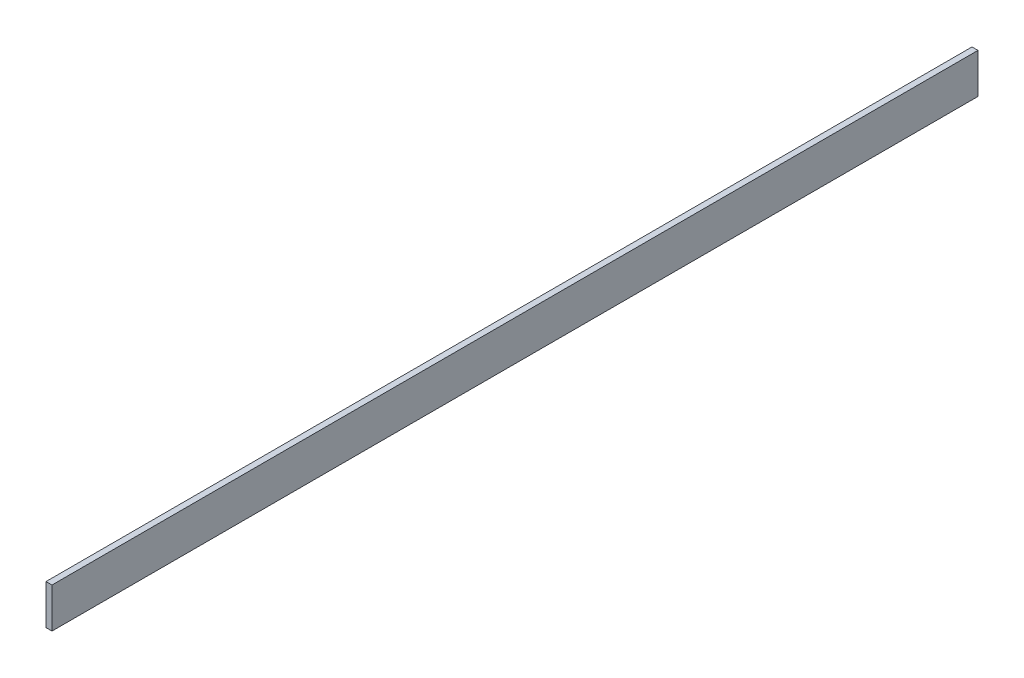
SolidWorks part; units mm, degrees
ref_plane "Face" through (0, 0, 0) normal (0, 0, 1) x (1, 0, 0)
ref_plane "Dessus" through (0, 0, 0) normal (0, 1, 0) x (1, 0, 0)
ref_plane "Droite" through (0, 0, 0) normal (1, 0, 0) x (0, 0, -1)
sketch "Esquisse1" plane through (0, 0, 0) normal (0, 0, 1) x (1, 0, 0)
  line L1 (0, 0) -> (3, 0)
  line L2 (0, 0) -> (0, 20)
  line L3 (0, 20) -> (3, 20)
  line L4 (3, 0) -> (3, 20)
  dimension "D1" = 3
  dimension "D2" = 20
extrude "Boss.-Extru.1" add sketch "Esquisse1" along normal blind 464
